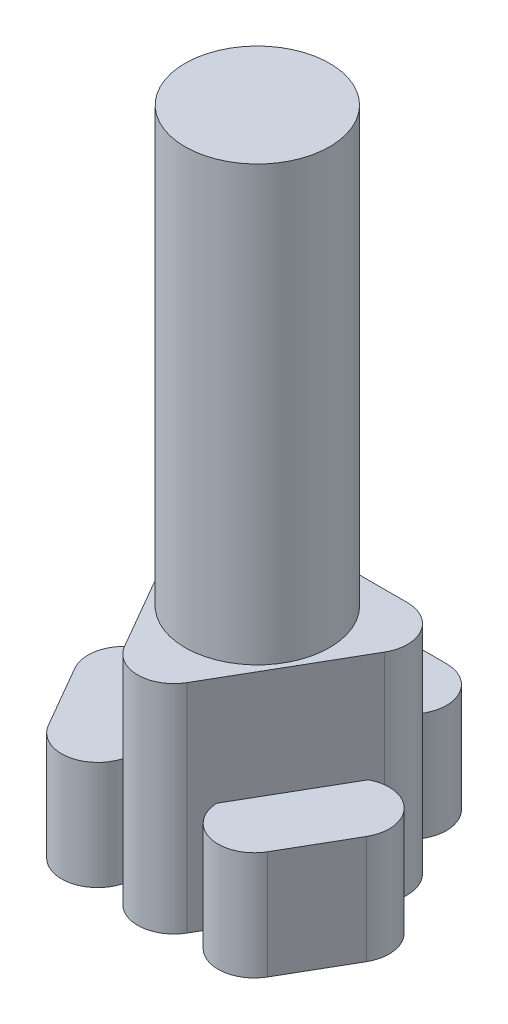
SolidWorks part; units mm, degrees
ref_plane "Front Plane" through (0, 0, 0) normal (0, 0, 1) x (1, 0, 0)
ref_plane "Top Plane" through (0, 0, 0) normal (0, 1, 0) x (1, 0, 0)
ref_plane "Right Plane" through (0, 0, 0) normal (1, 0, 0) x (0, 0, -1)
sketch "Sketch1" plane through (0, 0, 0) normal (0, 1, 0) x (1, 0, 0)
  line L0 (0.2866, 0.0655) -> (0.0866, -0.2809)
  line L1 (-0.0866, -0.2809) -> (-0.2866, 0.0655)
  line L2 (0.2, 0.2155) -> (-0.2, 0.2155)
  line L3 (0, -0.2309) -> (0.2, 0.1155) construction
  line L4 (0.2, 0.1155) -> (-0.2, 0.1155) construction
  line L5 (-0.2, 0.1155) -> (0, -0.2309) construction
  line L6 (0.2, 0.1155) -> (-0.1, -0.0577) construction
  line L7 (0, -0.2309) -> (0, 0.1155) construction
  arc A1 (-0.0866, -0.2809) -> (0.0866, -0.2809) centre (0, -0.2309) ccw
  arc A2 (0.2866, 0.0655) -> (0.2, 0.2155) centre (0.2, 0.1155) ccw
  arc A5 (-0.2, 0.2155) -> (-0.2866, 0.0655) centre (-0.2, 0.1155) ccw
  point P3 (0, 0)
  dimension "D2" = 0.4
  dimension "D3" = 0.4
  dimension "D1" = 0.4
  dimension "D4" = 0.1
extrude "Boss-Extrude1" add sketch "Sketch1" along normal blind 0.6
sketch "Sketch2" plane through (0, 0, 0) normal (0, 1, 0) x (1, 0, 0)
  line L0 (0.4031, -0.1018) -> (0.3031, -0.275)
  line L3 (0.1, 0.4232) -> (-0.1, 0.4232)
  line L4 (-0.3031, -0.275) -> (-0.4031, -0.1018)
  line L6 (0.1, 0.2232) -> (-0.1, 0.2232)
  line L7 (0.1299, -0.175) -> (0.2299, -0.0018)
  line L8 (-0.1299, -0.175) -> (-0.2299, -0.0018)
  arc A0 (-0.1, 0.2232) -> (-0.1, 0.4232) centre (-0.1, 0.3232) cw
  arc A1 (0.1, 0.2232) -> (0.1, 0.4232) centre (0.1, 0.3232) ccw
  arc A2 (-0.3031, -0.275) -> (-0.1299, -0.175) centre (-0.2165, -0.225) ccw
  arc A3 (-0.4031, -0.1018) -> (-0.2299, -0.0018) centre (-0.3165, -0.0518) cw
  arc A4 (0.4031, -0.1018) -> (0.2299, -0.0018) centre (0.3165, -0.0518) ccw
  arc A5 (0.3031, -0.275) -> (0.1299, -0.175) centre (0.2165, -0.225) cw
extrude "Boss-Extrude2" add sketch "Sketch2" along normal blind 0.3 separate body
sketch "Sketch3" plane through (0, 0.6, 0) normal (0, 1, 0) x (1, 0, 0)
  circle A0 centre (0, 0) radius 0.2
  dimension "D1" = 0.4
extrude "Boss-Extrude3" add sketch "Sketch3" along normal blind 1.2
